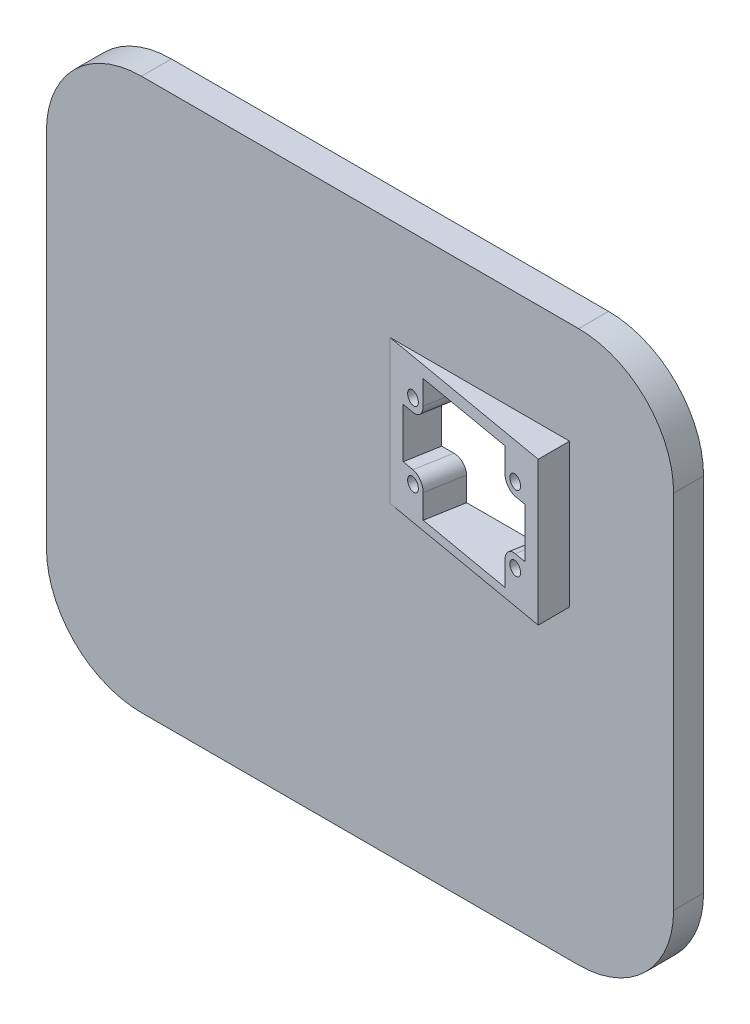
SolidWorks part; units mm, degrees
ref_plane "Front Plane" through (0, 0, 0) normal (0, 0, 1) x (1, 0, 0)
ref_plane "Top Plane" through (0, 0, 0) normal (0, 1, 0) x (1, 0, 0)
ref_plane "Right Plane" through (0, 0, 0) normal (1, 0, 0) x (0, 0, -1)
sketch "Sketch1" plane through (0, 0, 0) normal (0, 0, 1) x (1, 0, 0)
  line L0 (-52.3875, 0) -> (52.3875, 0) construction
  line L1 (0, 46.0375) -> (0, -46.0375) construction
  line L2 (-36.5125, 46.0375) -> (36.5125, 46.0375)
  line L3 (-52.3875, 30.1625) -> (-52.3875, -30.1625)
  line L4 (52.3875, 30.1625) -> (52.3875, -30.1625)
  line L5 (-36.5125, -46.0375) -> (36.5125, -46.0375)
  arc A0 (-36.5125, 46.0375) -> (-52.3875, 30.1625) centre (-36.5125, 30.1625) ccw
  arc A1 (36.5125, 46.0375) -> (52.3875, 30.1625) centre (36.5125, 30.1625) cw
  arc A2 (36.5125, -46.0375) -> (52.3875, -30.1625) centre (36.5125, -30.1625) ccw
  arc A3 (-36.5125, -46.0375) -> (-52.3875, -30.1625) centre (-36.5125, -30.1625) cw
  point P5 (0, 0)
  point P6 (0, 0)
  point P22 (-52.3875, 0)
  dimension "D3" = 15.875
  dimension "D4" = 15.875
  dimension "D1" = 104.775
  dimension "D2" = 92.075
extrude "Boss-Extrude1" add sketch "Sketch1" along normal blind 5
sketch "Sketch5" plane through (0, 0, 0) normal (0, 1, 0) x (1, 0, 0)
  line L0 (5, -5) -> (35, -10.2331)
  line L1 (35, -10.2331) -> (35, -5)
  line L2 (35, -5) -> (5, -5)
  line L3 (0, 0) -> (0, -5) construction
  line L4 (36.5125, -5) -> (-36.5125, -5) construction
  line L5 (-52.3875, -5) -> (-36.5125, -5) construction
  dimension "D1" = 30
  dimension "D2" = 5
  dimension "D3" = 9.895
extrude "Boss-Extrude2" add sketch "Sketch5" along normal blind 24 from offset 5
sketch "Sketch7" plane through (-0.6988, 0, 4.0059) normal (-0.1718, 0, 0.9851) x (0.9851, 0, 0.1718)
  line L0 (21.0113, 29) -> (21.0113, 5) construction
  line L1 (5.7848, 29) -> (36.2378, 29) construction
  line L2 (5.7848, 5) -> (36.2378, 5) construction
  line L3 (5.7848, 16.75) -> (36.2378, 16.75) construction
  line L4 (5.7848, 29) -> (5.7848, 5) construction
  line L5 (36.2378, 29) -> (36.2378, 5) construction
  line L7 (29.4113, 27) -> (12.6113, 27)
  line L8 (8.5113, 20.9) -> (8.5113, 12.6)
  line L9 (8.5113, 20.9) -> (10.5113, 20.9)
  line L10 (12.6113, 27) -> (12.6113, 23)
  line L11 (29.4113, 27) -> (29.4113, 23)
  line L12 (33.5113, 20.9) -> (31.5113, 20.9)
  line L13 (33.5113, 20.9) -> (33.5113, 12.6)
  line L14 (33.5113, 12.6) -> (31.5113, 12.6)
  line L15 (29.4113, 6.5) -> (29.4113, 10.5)
  line L16 (12.6113, 6.5) -> (12.6113, 10.5)
  line L17 (8.5113, 12.6) -> (10.5113, 12.6)
  line L18 (29.4113, 6.5) -> (12.6113, 6.5)
  line L21 (10.5113, 23) -> (12.6113, 23) construction
  line L22 (10.5113, 23) -> (10.5113, 20.9) construction
  arc A0 (10.5113, 20.9) -> (12.6113, 23) centre (10.5113, 23) ccw
  circle A1 centre (10.5113, 23) radius 1.1
  circle A2 centre (31.5113, 23) radius 1.1
  arc A3 (31.5113, 20.9) -> (29.4113, 23) centre (31.5113, 23) cw
  arc A4 (31.5113, 12.6) -> (29.4113, 10.5) centre (31.5113, 10.5) ccw
  circle A5 centre (31.5113, 10.5) radius 1.1
  circle A6 centre (10.5113, 10.5) radius 1.1
  arc A7 (10.5113, 12.6) -> (12.6113, 10.5) centre (10.5113, 10.5) cw
  point P20 (21.0113, 6.5)
  point P29 (21.0113, 27)
  point P38 (33.5113, 16.75)
  point P41 (8.5113, 16.75)
  dimension "D2" = 10.25
  dimension "D3" = 2.2
  dimension "D4" = 10.5
  dimension "D6" = 2.1
  dimension "D1" = 6.25
  dimension "D5" = 12.5
  dimension "D7" = 2
extrude "Cut-Extrude1" cut sketch "Sketch7" against normal through all
equation "\"r\"= 12"
equation "\"D1@Sketch2\"= \"r\""
